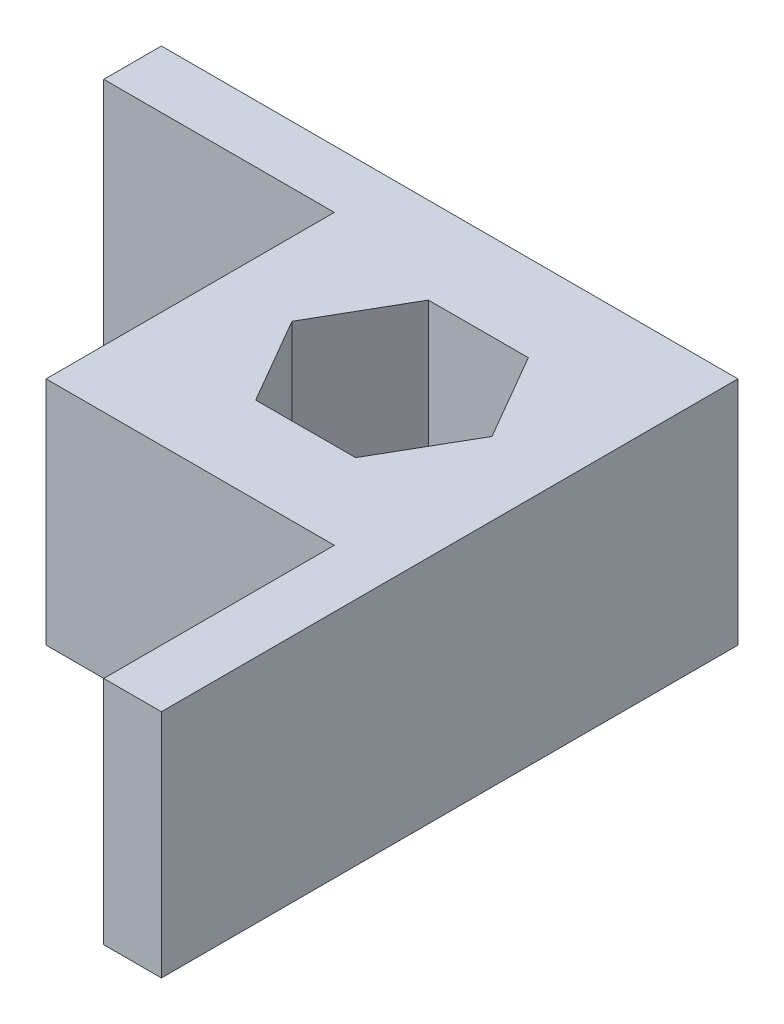
SolidWorks part; units mm, degrees
ref_plane "Front Plane" through (0, 0, 0) normal (0, 0, 1) x (1, 0, 0)
ref_plane "Top Plane" through (0, 0, 0) normal (0, 1, 0) x (1, 0, 0)
ref_plane "Right Plane" through (0, 0, 0) normal (1, 0, 0) x (0, 0, -1)
sketch "Sketch2" plane through (0, 0, 0) normal (0, 1, 0) x (1, 0, 0)
  line L0 (0, 0) -> (50, 0)
  line L1 (50, 0) -> (50, -50)
  line L2 (50, -50) -> (45, -50)
  line L3 (45, -50) -> (45, -30)
  line L4 (45, -30) -> (20, -30)
  line L5 (20, -30) -> (20, -5)
  line L6 (20, -5) -> (0, -5)
  line L7 (0, -5) -> (0, 0)
  dimension "D1" = 50
  dimension "D2" = 20
  dimension "D3" = 50
  dimension "D4" = 20
  dimension "D5" = 5
  dimension "D6" = 5
extrude "Boss-Extrude1" add sketch "Sketch2" along normal blind 20
sketch "Sketch3" plane through (0, 20, 0) normal (0, 1, 0) x (1, 0, 0)
  line L0 (50, 0) -> (20, -30) construction
  line L2 (39.3412, -22.4936) -> (43.6602, -14.9872)
  line L3 (43.6602, -14.9872) -> (39.319, -7.4936)
  line L4 (39.319, -7.4936) -> (30.6588, -7.5064)
  line L5 (30.6588, -7.5064) -> (26.3398, -15.0128)
  line L6 (26.3398, -15.0128) -> (30.681, -22.5064)
  line L7 (30.681, -22.5064) -> (39.3412, -22.4936)
  circle A0 centre (35, -15) radius 8.6603 construction
extrude "Cut-Extrude1" cut sketch "Sketch3" against normal blind 20
